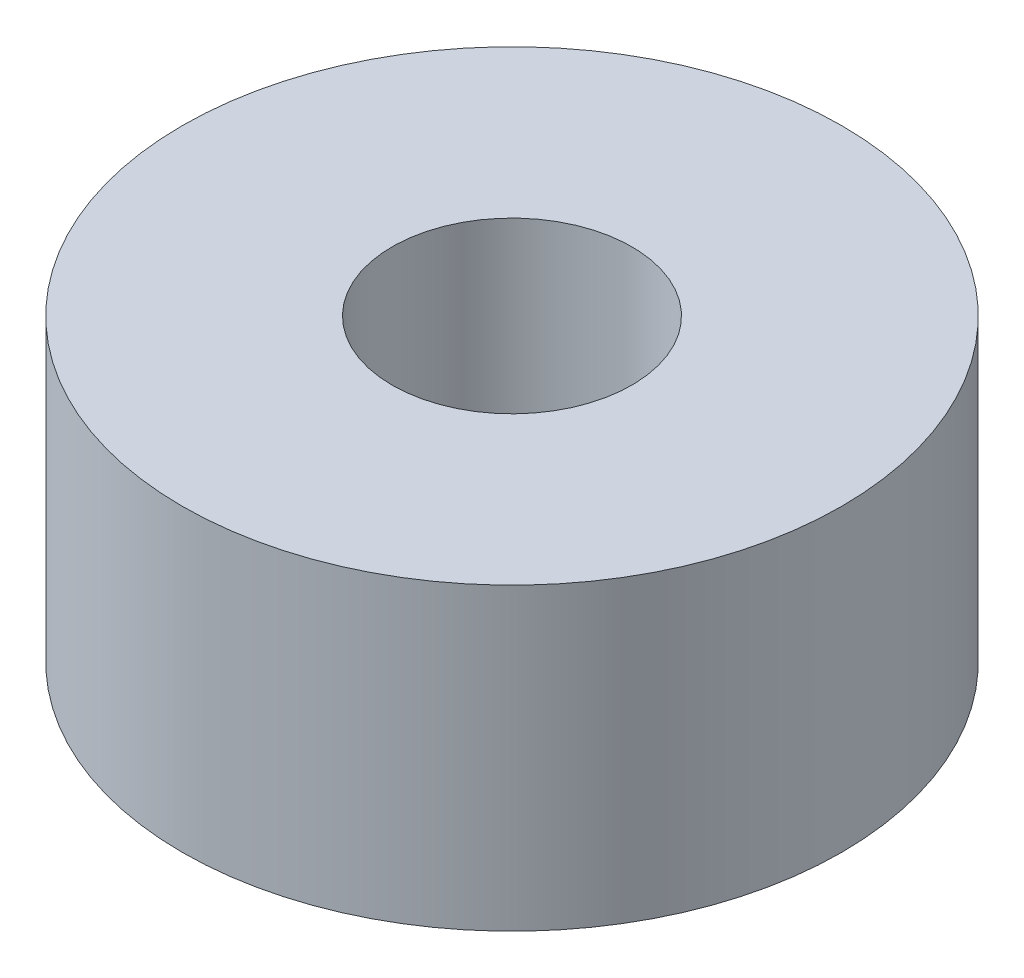
SolidWorks part; units mm, degrees
ref_plane "前视基准面" through (0, 0, 0) normal (0, 0, 1) x (1, 0, 0)
ref_plane "上视基准面" through (0, 0, 0) normal (0, 1, 0) x (1, 0, 0)
ref_plane "右视基准面" through (0, 0, 0) normal (1, 0, 0) x (0, 0, -1)
other "Configuration Table"
sketch "草图1" plane through (0, 0, 0) normal (0, 1, 0) x (1, 0, 0)
  circle A0 centre (0, 0) radius 4
  circle A1 centre (0, 0) radius 11
  dimension "D1" = 8
  dimension "D2" = 22
extrude "凸台-拉伸1" add sketch "草图1" along normal blind 10
